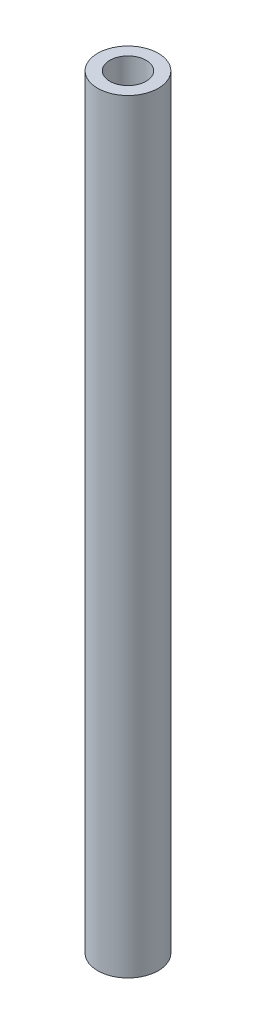
SolidWorks part; units mm, degrees
ref_plane "前视基准面" through (0, 0, 0) normal (0, 0, 1) x (1, 0, 0)
ref_plane "上视基准面" through (0, 0, 0) normal (0, 1, 0) x (1, 0, 0)
ref_plane "右视基准面" through (0, 0, 0) normal (1, 0, 0) x (0, 0, -1)
sketch "草图1" plane through (0, 0, 0) normal (0, 1, 0) x (1, 0, 0)
  circle A0 centre (0, 0) radius 2.5
  circle A1 centre (0, 0) radius 1.5
  dimension "D1" = 3
  dimension "D2" = 5
extrude "凸台-拉伸1" add sketch "草图1" along normal blind 63
